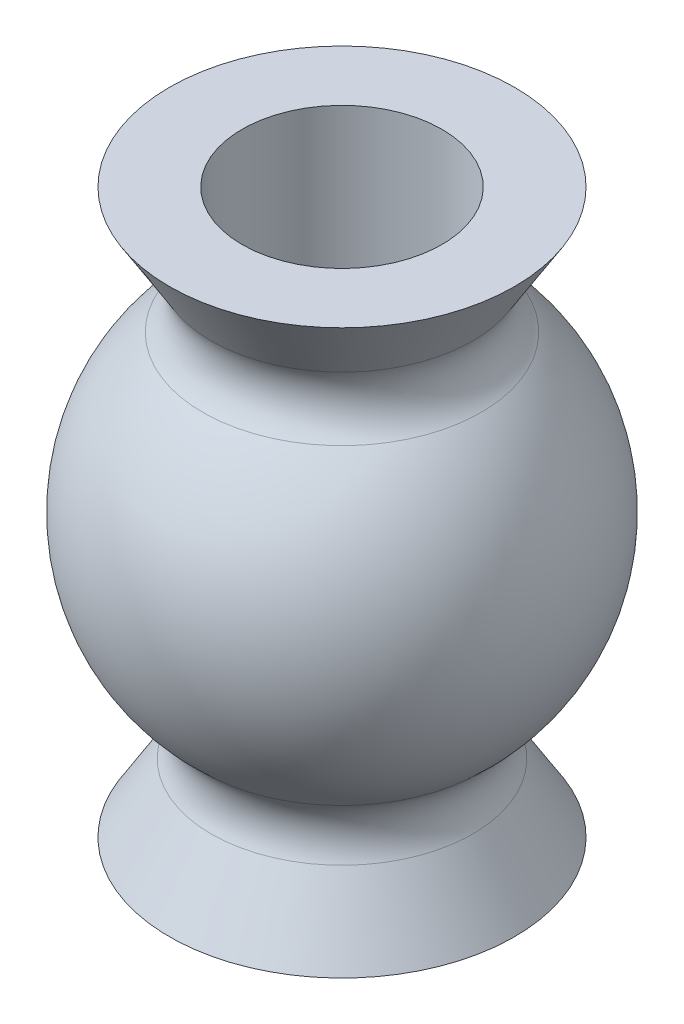
SolidWorks part; units mm, degrees
material "6061-T6 (SS)"
ref_plane "Front Plane" through (0, 0, 0) normal (0, 0, 1) x (1, 0, 0)
ref_plane "Top Plane" through (0, 0, 0) normal (0, 1, 0) x (1, 0, 0)
ref_plane "Right Plane" through (0, 0, 0) normal (1, 0, 0) x (0, 0, -1)
sketch "Sketch1" plane through (0, 0, 0) normal (0, 0, 1) x (1, 0, 0)
  line L0 (0, 0) -> (0, 7.874) construction
  line L3 (-1.397, 7.874) -> (-2.413, 7.874)
  line L4 (-1.397, 0) -> (-2.413, 0)
  line L5 (-2.413, 0) -> (-1.524, 1.4451)
  line L6 (-2.413, 7.874) -> (-1.524, 6.4289)
  line L8 (-1.397, 7.874) -> (-1.397, 0)
  arc A0 (-1.524, 6.4289) -> (-1.524, 1.4451) centre (0, 3.937) ccw
  dimension "D3" = 5.842
  dimension "D1" = 7.874
  dimension "D2" = 1.397
  dimension "D4" = 2.413
revolve "Revolve1" add sketch "Sketch1" angle 360 about L0
fillet "Fillet1" radius 0.635 2 edges at (0, 1.4451, -1.524) (0, 6.4289, -1.524)
